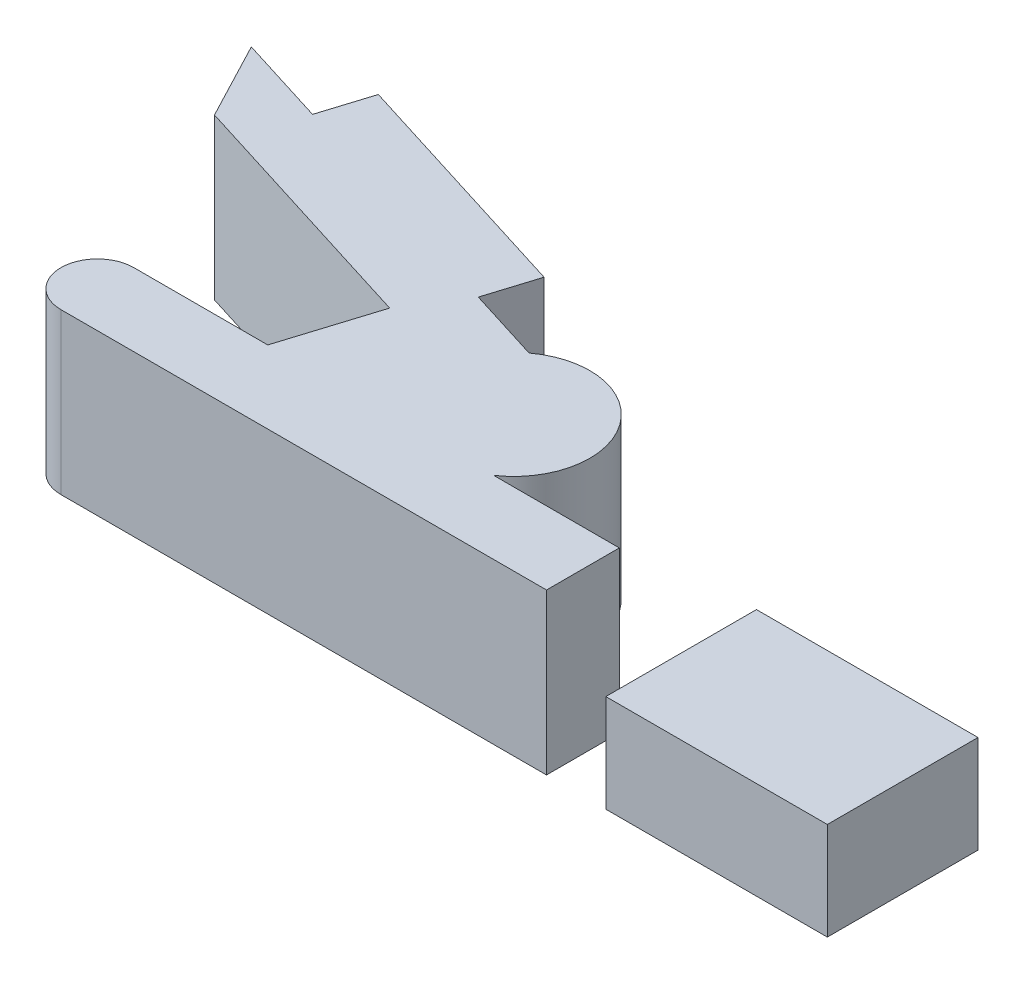
SolidWorks part; units mm, degrees
ref_plane "前视基准面" through (0, 0, 0) normal (0, 0, 1) x (1, 0, 0)
ref_plane "上视基准面" through (0, 0, 0) normal (0, 1, 0) x (1, 0, 0)
ref_plane "右视基准面" through (0, 0, 0) normal (1, 0, 0) x (0, 0, -1)
sketch "草图1" plane through (0, 0, 0) normal (0, 1, 0) x (1, 0, 0)
  line L0 (-88.6336, 48.9805) -> (-80.2845, 33.0413)
  line L1 (-61.3629, -2.4926) -> (-33.7751, -2.4926)
  line L3 (-61.3629, -17.4926) -> (38.6371, -17.4926)
  line L4 (38.6371, -2.4926) -> (38.6371, -17.4926)
  line L5 (-80.2845, 33.0413) -> (-27.7966, 16.6388)
  line L6 (-27.7966, 16.6388) -> (-33.7751, -2.4926)
  line L7 (-88.6336, 48.9805) -> (-70.2877, 43.2474)
  line L8 (-70.2877, 43.2474) -> (-67.0633, 53.5656)
  line L9 (-67.0633, 53.5656) -> (-17.4061, 38.0478)
  line L10 (-17.4061, 38.0478) -> (-20.6306, 27.7295)
  line L11 (-20.6306, 27.7295) -> (-5.4242, 22.9775)
  line L12 (12.7438, -2.4926) -> (38.6371, -2.4926)
  line L14 (50.8496, 13.5371) -> (96.4794, 13.5371)
  line L15 (50.8496, 13.5371) -> (50.8496, -17.4926)
  line L16 (50.8496, -17.4926) -> (96.4794, -17.4926)
  line L17 (96.4794, 13.5371) -> (96.4794, -17.4926)
  arc A0 (-61.3629, -2.4926) -> (-61.3629, -17.4926) centre (-61.3629, -9.9926) ccw
  arc A1 (12.7438, -2.4926) -> (-5.4242, 22.9775) centre (3.9657, 10.4607) ccw
  dimension "D1" = 15
  dimension "D2" = 100
extrude "凸台-拉伸1" add sketch "草图1" along normal blind 33
sketch "草图4" plane through (0, 0, 17.4926) normal (0, 0, 1) x (1, 0, 0)
  line L0 (96.4794, 33) -> (96.4794, 0) construction
  line L1 (50.8496, 33) -> (96.4794, 33)
  line L2 (50.8496, 33) -> (50.8496, 20.0949)
  line L3 (50.8496, 20.0949) -> (96.4794, 20.0949)
  line L4 (96.4794, 33) -> (96.4794, 20.0949)
extrude "切除-拉伸1" cut sketch "草图4" against normal blind 33
